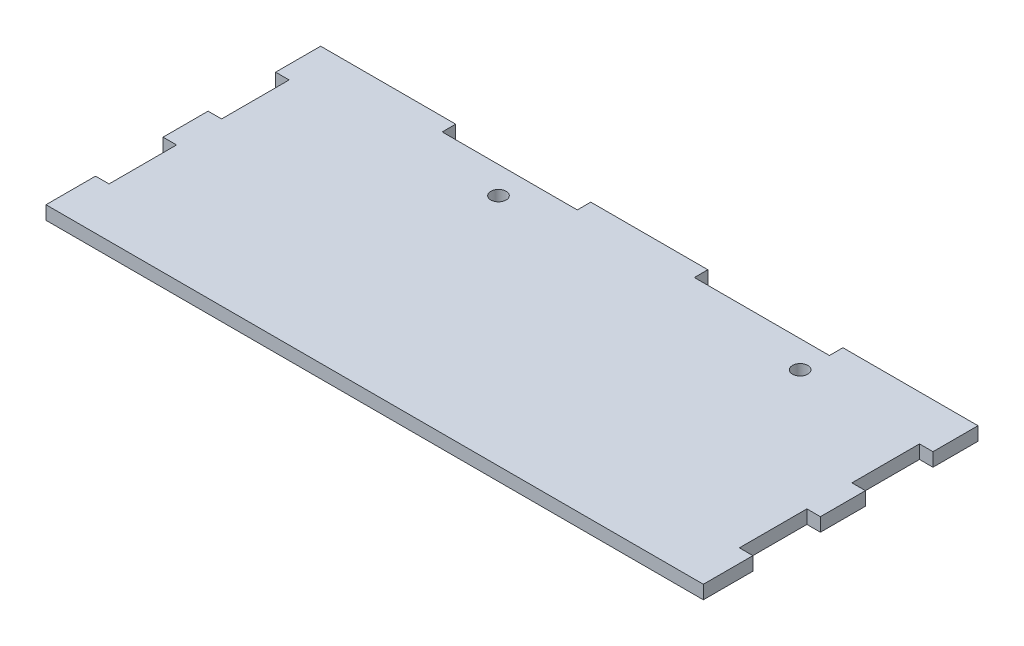
SolidWorks part; units mm, degrees
ref_plane "Front Plane" through (0, 0, 0) normal (0, 0, 1) x (1, 0, 0)
ref_plane "Top Plane" through (0, 0, 0) normal (0, 1, 0) x (1, 0, 0)
ref_plane "Right Plane" through (0, 0, 0) normal (1, 0, 0) x (0, 0, -1)
other "Configuration Table"
sketch "Sketch1" plane through (0, 0, 0) normal (0, 1, 0) x (1, 0, 0)
  line L1 (73, -30.5) -> (-73, -30.5)
  line L2 (73, -30.5) -> (73, 30.5)
  line L3 (73, 30.5) -> (-73, 30.5)
  line L4 (-73, -30.5) -> (-73, 30.5)
  line L5 (73, -30.5) -> (-73, 30.5) construction
  line L6 (73, 30.5) -> (-73, -30.5) construction
  point P0 (0, 0)
  dimension "D1" = 61
  dimension "D2" = 146
extrude "Boss-Extrude1" add sketch "Sketch1" along normal blind 3
sketch "Sketch2" plane through (0, 3, 0) normal (0, 1, 0) x (1, 0, 0)
  line L0 (-73, 30.5) -> (-73, -30.5) construction
  line L1 (73, -30.5) -> (73, 30.5) construction
  line L2 (-73, -30.5) -> (73, -30.5) construction
  line L3 (-73, 20.5) -> (-70, 20.5)
  line L4 (-70, 20.5) -> (-70, 5.5)
  line L5 (-70, 5.5) -> (-73, 5.5)
  line L6 (-73, 5.5) -> (-73, 20.5)
  line L7 (-70, -4.5) -> (-70, -19.5)
  line L8 (-70, -19.5) -> (-73, -19.5)
  line L9 (-73, -19.5) -> (-73, -4.5)
  line L10 (-73, -4.5) -> (-70, -4.5)
  line L11 (73, 20.5) -> (70, 20.5)
  line L12 (70, 20.5) -> (70, 5.5)
  line L13 (70, 5.5) -> (73, 5.5)
  line L14 (70, -4.5) -> (70, -19.5)
  line L15 (70, -19.5) -> (73, -19.5)
  line L16 (73, -19.5) -> (73, -4.5)
  line L17 (73, -4.5) -> (70, -4.5)
  line L18 (73, 20.5) -> (73, 5.5)
  line L19 (-43, 30.5) -> (-43, 27.5)
  line L20 (73, 30.5) -> (-73, 30.5) construction
  line L21 (-43, 27.5) -> (-13, 27.5)
  line L22 (-13, 27.5) -> (-13, 30.5)
  line L23 (-13, 30.5) -> (-43, 30.5)
  line L24 (13, 27.5) -> (43, 27.5)
  line L25 (43, 27.5) -> (43, 30.5)
  line L26 (43, 30.5) -> (13, 30.5)
  line L27 (13, 30.5) -> (13, 27.5)
  circle A0 centre (-24.5, 21.5) radius 1.7
  circle A1 centre (42.5, 21.5) radius 1.7
  dimension "D1" = 48.5
  dimension "D2" = 30.5
  dimension "D3" = 52
  dimension "D4" = 52
  dimension "D5" = 15
  dimension "D6" = 10
  dimension "D7" = 10
  dimension "D12" = 3
  dimension "D13" = 3
  dimension "D14" = 30
  dimension "D15" = 30
  dimension "D16" = 30
extrude "Cut-Extrude1" cut sketch "Sketch2" against normal blind 10
